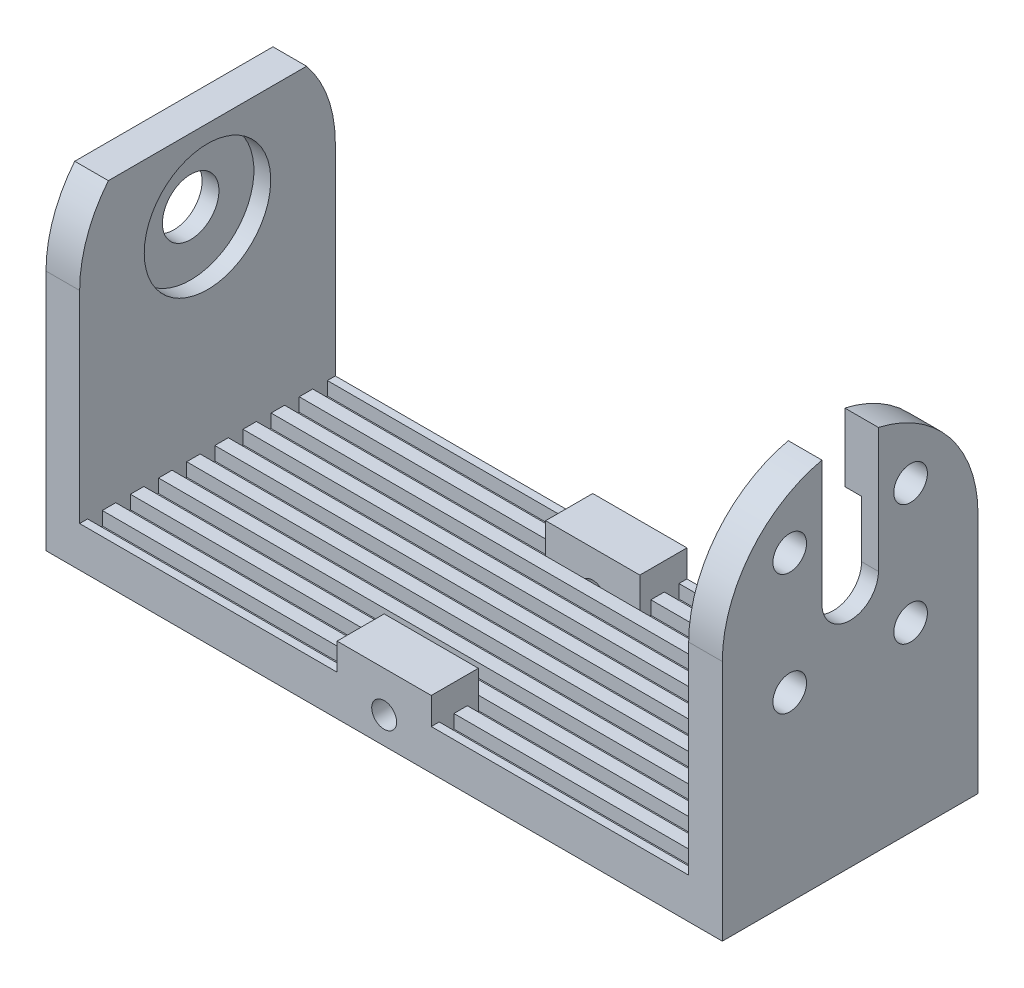
SolidWorks part; units mm, degrees
material "Custom Plastic"
ref_plane "Front Plane" through (0, 0, 0) normal (0, 0, 1) x (1, 0, 0)
ref_plane "Top Plane" through (0, 0, 0) normal (0, 1, 0) x (1, 0, 0)
ref_plane "Right Plane" through (0, 0, 0) normal (1, 0, 0) x (0, 0, -1)
sketch "Sketch1" plane through (0, 0, 0) normal (0, 1, 0) x (1, 0, 0)
  line L1 (25.13, -12) -> (-25.13, -12)
  line L2 (25.13, -12) -> (25.13, 12)
  line L3 (25.13, 12) -> (-25.13, 12)
  line L4 (-25.13, -12) -> (-25.13, 12)
  line L5 (25.13, -12) -> (-25.13, 12) construction
  line L6 (25.13, 12) -> (-25.13, -12) construction
  point P0 (0, 0)
  dimension "D1" = 50.26
  dimension "D2" = 24
extrude "Boss-Extrude1" add sketch "Sketch1" along normal blind 2
sketch "Sketch2" plane through (0, 2, 0) normal (0, 1, 0) x (1, 0, 0)
  line L0 (-25.13, 12) -> (-25.13, -12) construction
  line L1 (-25.13, 12) -> (-25.13, -12)
  line L2 (25.13, -12) -> (25.13, 12) construction
  line L3 (25.13, -12) -> (25.13, 12)
  line L4 (-22.63, 12) -> (-22.63, -12)
  line L5 (22.63, -12) -> (22.63, 12)
  line L6 (-25.13, 12) -> (-22.63, 12)
  line L7 (22.63, 12) -> (25.13, 12)
  line L8 (25.13, -12) -> (22.63, -12)
  line L9 (-22.63, -12) -> (-25.13, -12)
  dimension "D1" = 2.5
  dimension "D2" = 2.5
extrude "Boss-Extrude2" add sketch "Sketch2" along normal blind 22
sketch "Sketch3" plane through (25.13, 0, 0) normal (1, 0, 0) x (0, 0, -1)
  line L0 (-12, 24) -> (12, 24) construction
  line L2 (12, 24) -> (12, 0) construction
  circle A0 centre (0, 18) radius 2.1
  dimension "D1" = 4.2
  dimension "D2" = 6
  dimension "D3" = 12
extrude "Cut-Extrude1" cut sketch "Sketch3" against normal through all
sketch "Sketch4" plane through (22.63, 0, 0) normal (-1, 0, 0) x (0, 0, 1)
  circle A0 centre (0, 18) radius 4.7
  dimension "D1" = 9.4
extrude "Cut-Extrude2" cut sketch "Sketch4" against normal blind 1.25
ref_plane "Plane1" through (0, 0, 0) normal (-1, 0, 0) x (0, 0, 1)
mirror "Mirror1" about plane through (0, 0, 0) normal (-1, 0, 0) of "Cut-Extrude2"
sketch "Sketch5" plane through (25.13, 0, 0) normal (1, 0, 0) x (0, 0, -1)
  line L0 (0, 12.1464) -> (0, 27.0231) construction
  line L1 (0, 18) -> (-15.0451, 18) construction
  circle A0 centre (4.4902, 13.5099) radius 1.25
  circle A1 centre (-4.4901, 13.5099) radius 1.25
  circle A2 centre (-4.4901, 22.4901) radius 1.25
  circle A3 centre (4.4901, 22.4901) radius 1.25
  dimension "D1" = 2.5
  dimension "D2" = 8.9803
  dimension "D4" = 2.5
  dimension "D5" = 2.5
  dimension "D6" = 2.5
  dimension "D3" = 8.9803
  dimension "D7" = 4.4901
  dimension "D8" = 4.4901
extrude "Cut-Extrude3" cut sketch "Sketch5" against normal up to next
sketch "Sketch6" plane through (25.13, 0, 0) normal (1, 0, 0) x (0, 0, -1)
  line L0 (-2.1, 18) -> (-2.1, 24)
  line L1 (-12, 24) -> (12, 24) construction
  line L2 (-2.1, 24) -> (2.1, 24)
  line L3 (2.1, 24) -> (2.1, 18)
  circle A0 centre (0, 18) radius 2.1 construction
  arc A1 (-2.1, 18) -> (2.1, 18) centre (0, 18) ccw
extrude "Cut-Extrude4" cut sketch "Sketch6" against normal up to next
sketch "Sketch7" plane through (0, 2, 0) normal (0, 1, 0) x (1, 0, 0)
  line L65 (22.63, 12) -> (22.63, -12) construction
  line L67 (-22.63, -12) -> (22.63, -12)
  line L68 (-22.63, -12) -> (-22.63, -11)
  line L69 (-22.63, -11) -> (22.63, -11)
  line L70 (22.63, -12) -> (22.63, -11)
  dimension "D1" = 1
extrude "Boss-Extrude3" add sketch "Sketch7" along normal blind 1
pattern_linear "LPattern3" count 12 spacing 2.0909 along (0, 0, -1) of "Boss-Extrude3"
sketch "Sketch9" plane through (25.13, 0, 0) normal (1, 0, 0) x (0, 0, -1)
  line L0 (2.1, 24) -> (12, 24) construction
  line L1 (-12, 24) -> (-2.1, 24) construction
  line L2 (2.1, 24) -> (7.3655, 24)
  line L3 (-7.3655, 24) -> (-2.1, 24)
  line L4 (-12, 0) -> (12, 0) construction
  line L5 (-2.1, 24) -> (-2.1, 27.265)
  line L6 (2.1, 24) -> (2.1, 27.265)
  arc A0 (-2.1, 27.265) -> (-7.3655, 24) centre (0, 18) ccw
  arc A2 (7.3655, 24) -> (2.1, 27.265) centre (0, 18) ccw
  dimension "D1" = 19
  dimension "D2" = 18
extrude "Boss-Extrude4" add sketch "Sketch9" against normal up to surface (2.5 mm away) up to face at (22.63, 22.4901, -5.7401)
sketch "Sketch10" plane through (25.13, 0, 0) normal (1, 0, 0) x (0, 0, -1)
  line L1 (-9.5, 18) -> (-9.5, 0)
  line L3 (-12, 0) -> (12, 0) construction
  line L4 (-9.5, 0) -> (-12, 0)
  line L5 (-12, 0) -> (-12, 24)
  line L6 (-12, 24) -> (-9.5, 24)
  line L7 (-12, 24) -> (-7.3655, 24) construction
  line L10 (7.3655, 24) -> (12, 24) construction
  line L11 (9.5, 24) -> (12, 24)
  line L12 (12, 24) -> (12, 0)
  line L13 (12, 0) -> (9.5, 0)
  line L14 (9.5, 0) -> (9.5, 18)
  line L15 (-9.5, 24) -> (-7.3655, 24)
  line L16 (9.5, 24) -> (7.3655, 24)
  arc A0 (-2.1, 27.265) -> (-7.3655, 24) centre (0, 18) ccw construction
  arc A1 (-7.3655, 24) -> (-9.5, 18) centre (0, 18) ccw
  arc A4 (9.5, 18) -> (7.3655, 24) centre (0, 18) ccw
  line M25 (-7.3655, 24) -> (-12, 24)
  line M26 (-12, 24) -> (-12, 0)
  line M27 (-12, 0) -> (12, 0)
extrude "Cut-Extrude6" cut sketch "Sketch10" against normal through all contours A1 L1 M25 M26 M27 | L16 L11 L12 L13 L14 A4
sketch "Sketch11" [suppressed] plane through (0, 3, 0) normal (0, 1, 0) x (1, 0, 0)
  line L0 (-19.13, 6.8182) -> (-19.13, -6.8182)
  line L1 (-22.63, 6.8182) -> (22.63, 6.8182) construction
  line L2 (22.63, -6.8182) -> (-22.63, -6.8182) construction
  line L3 (-19.13, -6.8182) -> (-5.5414, 0)
  line L5 (-5.5414, 0) -> (-19.13, 6.8182)
  line L14 (-29.3488, 0) -> (20.1675, 0) construction
  line L15 (0, -18.5163) -> (0, 15.7591) construction
  line L16 (0, 10.45) -> (0, -10.45) construction
  line L17 (-22.63, -0.5455) -> (-22.63, -1.5455) construction
  line L21 (3.2379, -2.3435) -> (12.1559, -6.8182)
  line L22 (-3.531, -2.3435) -> (3.2379, -2.3435)
  line L23 (-12.4491, -6.8182) -> (-3.531, -2.3435)
  line L24 (12.1559, -6.8182) -> (-12.4491, -6.8182)
  line L25 (22.63, -6.8182) -> (-22.63, -6.8182) construction
  line L26 (19.13, -6.8182) -> (5.5414, 0)
  line L27 (19.13, 6.8182) -> (19.13, -6.8182)
  line L28 (5.5414, 0) -> (19.13, 6.8182)
  line L29 (-3.531, 2.3435) -> (3.2379, 2.3435)
  line L30 (-12.4491, 6.8182) -> (-3.531, 2.3435)
  line L31 (12.1559, 6.8182) -> (-12.4491, 6.8182)
  line L32 (3.2379, 2.3435) -> (12.1559, 6.8182)
  dimension "D1" = 3.5
  dimension "D4" = 5.5414
  dimension "D6" = 2.9962
sketch "Sketch12" plane through (0, 3, 0) normal (0, 1, 0) x (1, 0, 0)
  line L0 (22.63, -9.5) -> (-22.63, -9.5) construction
  line L2 (3.5, -9.5) -> (3.5, -6)
  line L3 (3.5, -6) -> (-3.5, -6)
  line L4 (-3.5, -9.5) -> (-3.5, -6)
  line L7 (3.5, -9.5) -> (-3.5, -9.5)
  point P0 (0, -9.5)
  point P2 (0, -9.5)
  dimension "D1" = 7
  dimension "D2" = 3.5
extrude "Boss-Extrude5" add sketch "Sketch12" along normal blind 2 and the other way up to next
ref_plane "Plane2" through (0, 0, 0) normal (0, 0, 1) x (1, 0, 0)
mirror "Mirror2" about plane through (0, 0, 0) normal (0, 0, 1) of "Boss-Extrude5"
sketch "Sketch13" plane through (0, 0, -9.5) normal (0, 0, -1) x (-1, 0, 0)
  line L0 (25.13, 0) -> (-25.13, 0) construction
  circle A2 centre (0, 2) radius 0.925
  dimension "D1" = 2
  dimension "D2" = 1.85
extrude "Cut-Extrude7" cut sketch "Sketch13" against normal up to surface (3.5 mm away) up to face at (0, 3.5, -6)
sketch "Sketch14" plane through (0, 0, 9.5) normal (0, 0, 1) x (1, 0, 0)
  line L0 (-25.13, 0) -> (25.13, 0) construction
  circle A2 centre (0, 2) radius 0.925
  dimension "D1" = 1.85
  dimension "D2" = 2
extrude "Cut-Extrude9" cut sketch "Sketch14" against normal up to surface (3.5 mm away) up to face at (0, 3.5, 6)
equation "\"W\"= 24"
equation "\"L\"= 44"
equation "\"WT\"= 4"
equation "\"BT\"= 3"
equation "\"H\"= 24"
equation "\"BW\"=4"
equation "\"D1@Boss-Extrude1\"=\"BT\""
equation "\"D1@Boss-Extrude2\"=\"H\"- 2"
equation "\"SH\"= 4.2"
equation "\"D1@Sketch6\"=\"SH\""
equation "\"M2\"= 2"
equation "\"D2@Sketch9\"=\"H\"*(1/3)"
equation "\"D2@Sketch1\"=\"W\""
equation "\"D1@Sketch1\"=\"L\" +5+1.26"
equation "\"D1@Sketch3\"=\"SH\""
equation "\"D3@Sketch3\"=\"W\" /2"
